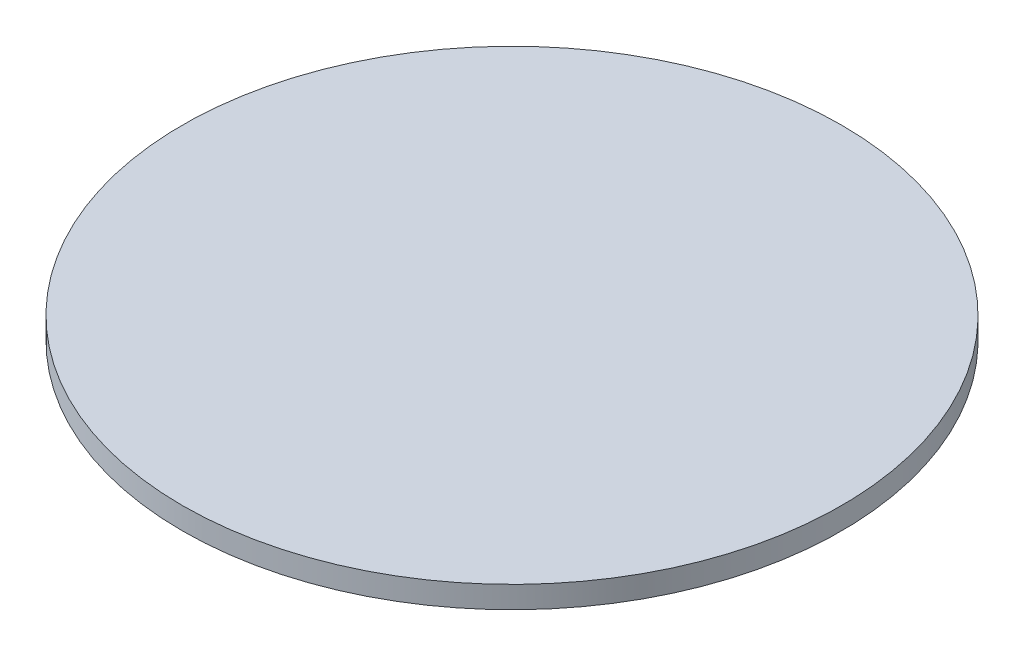
SolidWorks part; units mm, degrees
material "E-Glass Fiber"
ref_plane "Front Plane" through (0, 0, 0) normal (0, 0, 1) x (1, 0, 0)
ref_plane "Top Plane" through (0, 0, 0) normal (0, 1, 0) x (1, 0, 0)
ref_plane "Right Plane" through (0, 0, 0) normal (1, 0, 0) x (0, 0, -1)
sketch "Sketch1" plane through (0, 0, 0) normal (0, 1, 0) x (1, 0, 0)
  circle A1 centre (0, 0) radius 75
  dimension "D1" = 150
extrude "Boss-Extrude1" add sketch "Sketch1" along normal blind 5
